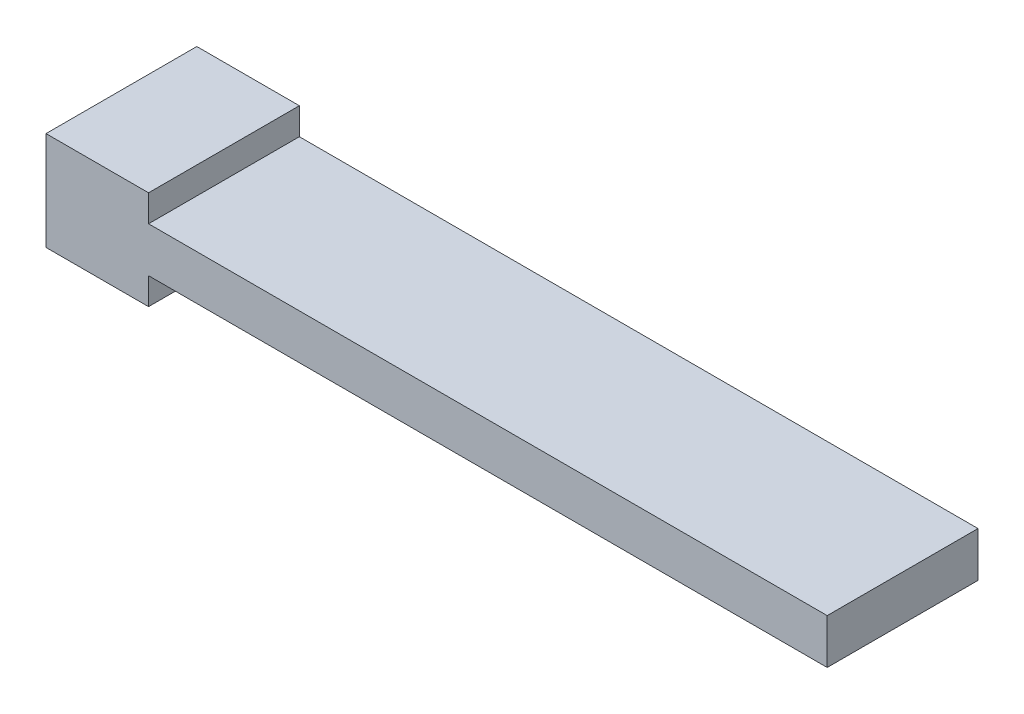
SolidWorks part; units mm, degrees
ref_plane "Front Plane" through (0, 0, 0) normal (0, 0, 1) x (1, 0, 0)
ref_plane "Top Plane" through (0, 0, 0) normal (0, 1, 0) x (1, 0, 0)
ref_plane "Right Plane" through (0, 0, 0) normal (1, 0, 0) x (0, 0, -1)
sketch "Sketch1" plane through (0, 0, 0) normal (0, 0, 1) x (1, 0, 0)
  line L0 (0, 0) -> (0, 2.9275)
  line L1 (0, 2.9275) -> (6.8, 2.9275)
  line L2 (6.8, 2.9275) -> (6.8, 1.1475)
  line L3 (6.8, 1.1475) -> (51.8, 1.1475)
  line L4 (51.8, 1.1475) -> (51.8, -1.8325)
  line L5 (51.8, -1.8325) -> (6.8, -1.8325)
  line L6 (6.8, -1.8325) -> (6.8, -3.6125)
  line L7 (6.8, -3.6125) -> (0, -3.6125)
  line L8 (0, -3.6125) -> (0, 0)
  dimension "D1" = 6.54
  dimension "D2" = 6.8
  dimension "D3" = 6.8
  dimension "D4" = 1.78
  dimension "D5" = 1.78
  dimension "D6" = 2.98
  dimension "D7" = 45
extrude "Boss-Extrude1" add sketch "Sketch1" along normal blind 10
